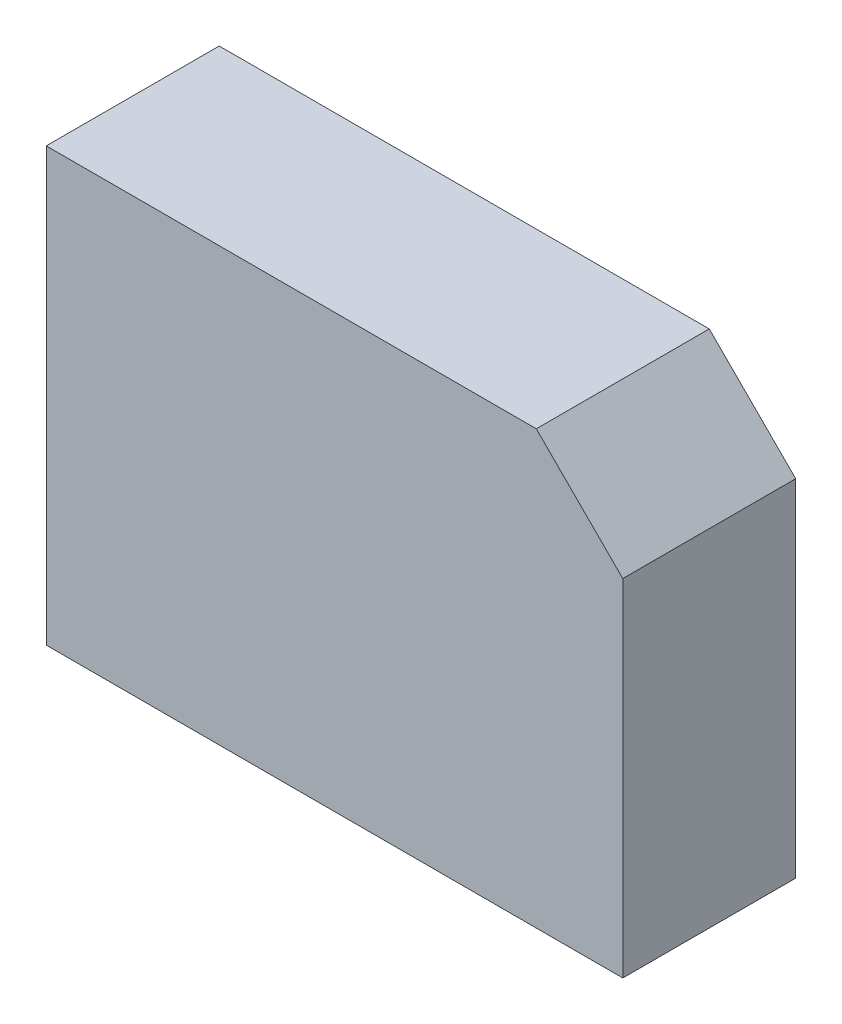
SolidWorks part; units mm, degrees
ref_plane "前视基准面" through (0, 0, 0) normal (0, 0, 1) x (1, 0, 0)
ref_plane "上视基准面" through (0, 0, 0) normal (0, 1, 0) x (1, 0, 0)
ref_plane "右视基准面" through (0, 0, 0) normal (1, 0, 0) x (0, 0, -1)
other "Configuration Table"
sketch "草图1" plane through (0, 0, 0) normal (0, 0, 1) x (1, 0, 0)
  line L1 (-10, 7.5) -> (10, 7.5)
  line L2 (-10, 7.5) -> (-10, -7.5)
  line L3 (-10, -7.5) -> (10, -7.5)
  line L4 (10, 7.5) -> (10, -7.5)
  line L5 (-10, 7.5) -> (10, -7.5) construction
  line L6 (-10, -7.5) -> (10, 7.5) construction
  point P0 (0, 0)
  point P5 (0, 0)
  dimension "D1" = 20
  dimension "D2" = 15
extrude "凸台-拉伸1" add sketch "草图1" along normal mid plane 6
chamfer "倒角1" distance 3 angle 45 1 edges at (10, 7.5, 0)
